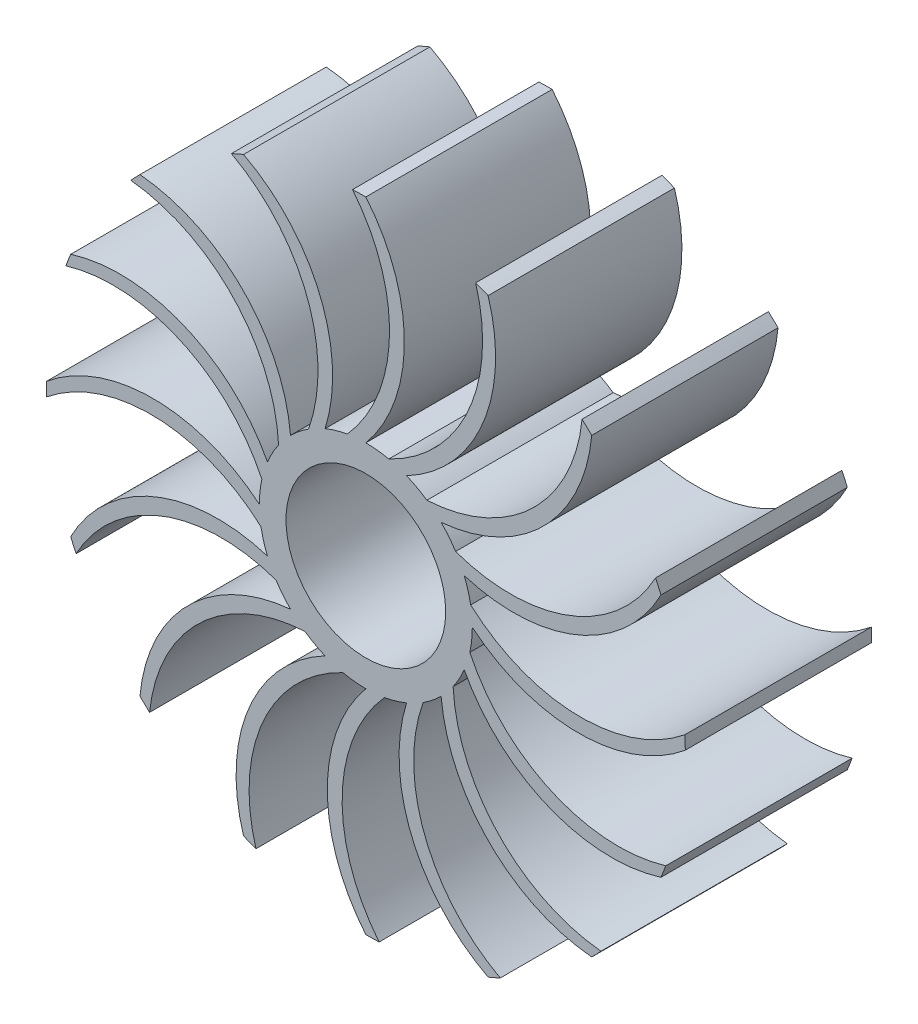
SolidWorks part; units mm, degrees
ref_plane "Płaszczyzna przednia" through (0, 0, 0) normal (0, 0, 1) x (1, 0, 0)
ref_plane "Płaszczyzna górna" through (0, 0, 0) normal (0, 1, 0) x (1, 0, 0)
ref_plane "Płaszczyzna prawa" through (0, 0, 0) normal (1, 0, 0) x (0, 0, -1)
sketch "Szkic1" plane through (0, 0, 0) normal (0, 0, 1) x (1, 0, 0)
  line L0 (0, 0) -> (-52.3828, 0) construction
  circle A0 centre (-26.1914, 0) radius 30
  circle A1 centre (-26.1914, 0) radius 40
extrude "Dodanie-wyciągnięcie1" add sketch "Szkic1" along normal blind 70
ref_plane "Płaszczyzna1" through (0, 0, 70) normal (0, 0, 1) x (1, 0, 0)
sketch "Szkic2" plane through (0, 0, 70) normal (0, 0, 1) x (1, 0, 0)
  circle A0 centre (-26.1914, 0) radius 120
  circle A1 centre (-26.1914, 0) radius 130
extrude "Dodanie-wyciągnięcie2" add sketch "Szkic2" against normal blind 70 separate body
sketch "Szkic3" plane through (0, 0, 70) normal (0, 0, 1) x (1, 0, 0)
  arc A2 (-66.1914, 0) -> (-146.1914, 0) centre (-106.1914, -48.0192) ccw
  circle A3 centre (-26.1914, 0) radius 40 construction
  circle A4 centre (-26.1914, 0) radius 120 construction
  arc A5 (-65.5789, -6.9732) -> (-146.0872, -4.9989) centre (-106.986, -53.0011) ccw
  arc A6 (-66.1914, 0) -> (-65.5789, -6.9732) centre (-26.1914, 0) ccw
  arc A7 (-146.0872, -4.9989) -> (-146.1914, 0) centre (-26.1914, 0) cw
  dimension "D1" = 5
  dimension "D2" = 7
extrude "Dodanie-wyciągnięcie3" add sketch "Szkic3" against normal blind 70
pattern_circular "Szyk kołowy1" count 16 over 360 about axis through (-26.1914, 0, 0) along (0, 0, 1) of "Dodanie-wyciągnięcie3"
sketch "Szkic4" plane through (0, 0, 70) normal (0, 0, 1) x (1, 0, 0)
  circle A0 centre (-26.1914, 0) radius 120
  circle A1 centre (-26.1914, 0) radius 130
extrude "Wytnij-wyciągnięcie1" cut sketch "Szkic4" against normal blind 70
